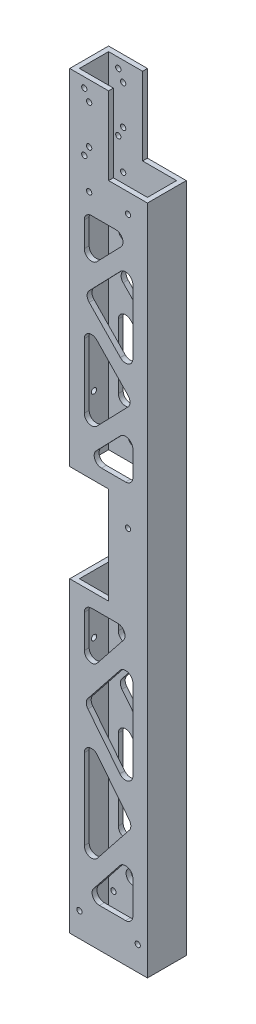
SolidWorks part; units mm, degrees
material "6061-T6 (SS)"
ref_plane "Front Plane" through (0, 0, 0) normal (0, 0, 1) x (1, 0, 0)
ref_plane "Top Plane" through (0, 0, 0) normal (0, 1, 0) x (1, 0, 0)
ref_plane "Right Plane" through (0, 0, 0) normal (1, 0, 0) x (0, 0, -1)
sketch "Sketch1" plane through (0, 0, 0) normal (0, 1, 0) x (1, 0, 0)
  line L0 (-22.225, 9.525) -> (-22.225, 12.7) construction
  line L1 (-25.4, -12.7) -> (25.4, -12.7)
  line L2 (-25.4, -12.7) -> (-25.4, 12.7)
  line L3 (-25.4, 12.7) -> (25.4, 12.7)
  line L4 (25.4, -12.7) -> (25.4, 12.7)
  line L5 (-25.4, -12.7) -> (25.4, 12.7) construction
  line L6 (-25.4, 12.7) -> (25.4, -12.7) construction
  line L7 (-22.225, -9.525) -> (22.225, -9.525)
  line L8 (-22.225, -9.525) -> (-22.225, 9.525)
  line L9 (-22.225, 9.525) -> (22.225, 9.525)
  line L10 (22.225, -9.525) -> (22.225, 9.525)
  line L11 (-22.225, -9.525) -> (22.225, 9.525) construction
  line L12 (-22.225, 9.525) -> (22.225, -9.525) construction
  line L13 (-22.225, 9.525) -> (-25.4, 9.525) construction
  point P0 (0, 0)
  point P6 (0, 0)
  dimension "D1" = 50.8
  dimension "D2" = 25.4
  dimension "D3" = 3.175
extrude "Boss-Extrude1" add sketch "Sketch1" along normal mid plane 489.585
sketch "Sketch2" plane through (0, 0, 12.7) normal (0, 0, 1) x (1, 0, 0)
  line L1 (25.4, 244.7925) -> (0, 244.7925)
  line L2 (25.4, 244.7925) -> (25.4, 193.9925)
  line L3 (25.4, 193.9925) -> (0, 193.9925)
  line L4 (0, 244.7925) -> (0, 193.9925)
  dimension "D1" = 25.4
  dimension "D2" = 50.8
extrude "Cut-Extrude1" cut sketch "Sketch2" against normal through all contours L3 L4 L1 L2
sketch "Sketch3" plane through (0, 0, 12.7) normal (0, 0, 1) x (1, 0, 0)
  line L0 (-25.4, 244.7925) -> (-25.4, -244.7925) construction
  line L1 (-25.4, -44.1325) -> (0, -44.1325)
  line L2 (-25.4, -44.1325) -> (-25.4, 19.3675)
  line L3 (-25.4, 19.3675) -> (0, 19.3675)
  line L4 (0, -44.1325) -> (0, 19.3675)
  line L5 (25.4, -244.7925) -> (-25.4, -244.7925) construction
  dimension "D1" = 63.5
  dimension "D2" = 25.4
  dimension "D3" = 200.66
extrude "Cut-Extrude2" cut sketch "Sketch3" against normal through all
hole_wizard "#8-32 Tapped Hole1" positions "Sketch5" profile "Sketch4" tap size "#8-32" standard "ANSI Inch" end condition through all
sketch "Sketch5" plane through (0, 0, -12.7) normal (0, 0, -1) x (-1, 0, 0)
  line L0 (12.7, 244.7925) -> (12.7, 50244.7925) construction
  line L1 (0, 244.7925) -> (25.4, 244.7925) construction
  line L2 (5.858, 181.2925) -> (-49994.142, 181.2925) construction
  line L3 (0, 192.4017) -> (0, 50192.4017) construction
  line L4 (0, 244.7925) -> (0, 193.9925) construction
  line L5 (12.7, 181.2925) -> (12.7, 206.6925) construction
  line L6 (12.7, 206.6925) -> (12.7, 232.0925) construction
  line L7 (12.7, 232.0925) -> (12.7, 244.7925) construction
  point P0 (12.7, 232.0925)
  point P2 (12.7, 206.6925)
  point P4 (12.7, 181.2925)
  point P6 (-12.7, 181.2925)
  point P13 (12.7, 244.7925)
  dimension "D1" = 25.4
  dimension "D2" = 25.4
  dimension "D3" = 12.7
sketch "Sketch4" plane through (-12.7, 232.0925, -12.7) normal (1, 0, 0) x (0, 1, 0)
  line L0 (0, 0) -> (0, 25.4)
  line L1 (0, 25.4) -> (1.7272, 25.4)
  line L2 (1.7272, 25.4) -> (1.7272, 0)
  line L5 (1.7272, 0) -> (0, 0)
  line L11 (0, -6.35) -> (0, 107.95) construction
  dimension "Thru Tap Drill Dia." = 3.4544
  dimension "Thru Tap Drill Depth" = 25.4
cosmetic thread "Hole Thread1" parameters "D2"=4.1656
cosmetic thread "Hole Thread2" parameters "D2"=4.1656
cosmetic thread "Hole Thread3" parameters "D2"=4.1656
cosmetic thread "Hole Thread4" parameters "D2"=4.1656
hole_wizard "#8-32 Tapped Hole2" positions "Sketch7" profile "Sketch6" tap size "#8-32" standard "ANSI Inch" end condition through all
sketch "Sketch7" plane through (0, 0, 12.7) normal (0, 0, 1) x (1, 0, 0)
  line L0 (-15.875, 200.3425) -> (-15.875, 50200.3425) construction
  line L1 (0, 219.3925) -> (-50000, 219.3925) construction
  line L2 (0, 244.7925) -> (0, 193.9925) construction
  point P0 (-15.875, 238.4425)
  point P2 (-15.875, 200.3425)
  point P11 (0, 219.3925)
  dimension "D1" = 38.1
  dimension "D2" = 15.875
sketch "Sketch6" plane through (-15.875, 238.4425, 12.7) normal (1, 0, 0) x (0, -1, 0)
  line L0 (0, 0) -> (0, 25.4)
  line L1 (0, 25.4) -> (1.7272, 25.4)
  line L2 (1.7272, 25.4) -> (1.7272, 0)
  line L5 (1.7272, 0) -> (0, 0)
  line L11 (0, -6.35) -> (0, 107.95) construction
  dimension "Thru Tap Drill Dia." = 3.4544
  dimension "Thru Tap Drill Depth" = 25.4
cosmetic thread "Hole Thread5" parameters "D2"=4.1656
cosmetic thread "Hole Thread6" parameters "D2"=4.1656
sketch "Sketch8" plane through (0, 0, 12.7) normal (0, 0, 1) x (1, 0, 0)
  line L0 (15.875, -179.4538) -> (15.875, -219.3925)
  line L1 (15.875, -219.3925) -> (-15.875, -219.3925)
  line L2 (-15.875, -219.3925) -> (15.875, -179.4538)
  line L5 (-25.4, -244.7925) -> (25.4, -244.7925) construction
  line L55 (1.209, 168.5925) -> (-49998.791, 168.5925) construction
  line L56 (-15.875, 168.5925) -> (15.875, 168.5925)
  line L57 (15.875, 168.5925) -> (-15.875, 135.7335)
  line L58 (-15.875, 135.7335) -> (-15.875, 168.5925)
  line L59 (-15.875, 122.0258) -> (15.875, 154.8848)
  line L60 (15.875, 154.8848) -> (15.875, 89.1668)
  line L61 (15.875, 89.1668) -> (-15.875, 122.0258)
  line L62 (-15.875, 108.3182) -> (15.875, 75.4592)
  line L63 (15.875, 75.4592) -> (-15.875, 42.6002)
  line L64 (-15.875, 42.6002) -> (-15.875, 108.3182)
  line L65 (-9.525, 235.2675) -> (-15.875, 235.2675)
  line L66 (-9.525, 184.4675) -> (-9.525, 235.2675)
  line L67 (15.875, 184.4675) -> (-9.525, 184.4675)
  line L68 (15.875, -235.2675) -> (15.875, 184.4675)
  line L69 (-15.875, -235.2675) -> (15.875, -235.2675)
  line L70 (-15.875, -53.6575) -> (-15.875, -235.2675)
  line L71 (9.525, -53.6575) -> (-15.875, -53.6575)
  line L72 (9.525, 28.8925) -> (9.525, -53.6575)
  line L73 (-15.875, 28.8925) -> (9.525, 28.8925)
  line L74 (-15.875, 235.2675) -> (-15.875, 28.8925)
  line L75 (-9.525, 235.2675) -> (-15.875, 235.2675) construction
  line L76 (-9.525, 184.4675) -> (-9.525, 235.2675) construction
  line L77 (15.875, 184.4675) -> (-9.525, 184.4675) construction
  line L78 (15.875, -235.2675) -> (15.875, 184.4675) construction
  line L79 (-15.875, -235.2675) -> (15.875, -235.2675) construction
  line L80 (-15.875, -53.6575) -> (-15.875, -235.2675) construction
  line L81 (9.525, -53.6575) -> (-15.875, -53.6575) construction
  line L82 (9.525, 28.8925) -> (9.525, -53.6575) construction
  line L83 (-15.875, 28.8925) -> (9.525, 28.8925) construction
  line L84 (-15.875, 235.2675) -> (-15.875, 28.8925) construction
  line L85 (-15.875, 28.8925) -> (15.875, 28.8925)
  line L86 (15.875, 28.8925) -> (15.875, 61.7515)
  line L87 (15.875, 61.7515) -> (-15.875, 28.8925)
  line L88 (-15.875, 135.7335) -> (-15.875, 108.3182) construction
  line L89 (15.875, 89.1668) -> (15.875, 61.7515) construction
  line L90 (15.875, 61.7515) -> (15.6894, 49.1955)
  line L91 (-15.875, -53.6575) -> (15.875, -53.6575)
  line L92 (15.875, -53.6575) -> (-15.875, -93.5962)
  line L93 (-15.875, -93.5962) -> (-15.875, -53.6575)
  line L94 (15.875, -68.9638) -> (-15.875, -108.9025)
  line L95 (-15.875, -108.9025) -> (15.875, -148.8412)
  line L96 (15.875, -148.8412) -> (15.875, -68.9638)
  line L97 (-15.875, -124.2088) -> (15.875, -164.1475)
  line L98 (15.875, -164.1475) -> (-15.875, -204.0862)
  line L99 (-15.875, -204.0862) -> (-15.875, -124.2088)
  line L103 (15.875, -148.8412) -> (15.875, -179.4538) construction
  line L104 (-15.875, -93.5962) -> (-15.875, -124.2088) construction
  dimension "D2" = 76.2
  dimension "D3" = 9.525
  dimension "D4" = 9.525
  dimension "D5" = 25.4
  dimension "D1" = 9.525
extrude "Cut-Extrude3" cut sketch "Sketch8" against normal through all
fillet "Fillet1" radius 4.7625 48 edges at (-15.875, 168.5925, -11.1125) (15.875, 168.5925, -11.1125) (-15.875, 135.7335, -11.1125) (-15.875, 108.3182, -11.1125) (15.875, 75.4592, -11.1125) (-15.875, 42.6002, -11.1125) (-15.875, 28.8925, -11.1125) (15.875, 61.7515, -11.1125) (15.875, 28.8925, -11.1125) (-15.875, -124.2088, -11.1125) (15.875, -164.1475, -11.1125) (-15.875, -204.0862, -11.1125) (15.875, -68.9638, -11.1125) (15.875, -148.8412, -11.1125) (-15.875, -108.9025, -11.1125) (-15.875, -53.6575, -11.1125) (15.875, -53.6575, -11.1125) (-15.875, -93.5962, -11.1125) (-15.875, 122.0258, -11.1125) (15.875, 154.8848, -11.1125) (15.875, 89.1668, -11.1125) (15.875, 168.5925, 11.1125) (-15.875, 135.7335, 11.1125) (-15.875, 168.5925, 11.1125) (15.875, 75.4592, 11.1125) (-15.875, 42.6002, 11.1125) (-15.875, 108.3182, 11.1125) (15.875, 28.8925, 11.1125) (-15.875, 28.8925, 11.1125) (15.875, 61.7515, 11.1125) (15.875, -164.1475, 11.1125) (-15.875, -204.0862, 11.1125) (-15.875, -124.2088, 11.1125) (-15.875, -108.9025, 11.1125) (15.875, -68.9638, 11.1125) (15.875, -148.8412, 11.1125) (15.875, -53.6575, 11.1125) (-15.875, -93.5962, 11.1125) (-15.875, -53.6575, 11.1125) (15.875, 154.8848, 11.1125) (15.875, 89.1668, 11.1125) (-15.875, 122.0258, 11.1125) (15.875, -179.4538, 11.1125) (15.875, -179.4538, -11.1125) (15.875, -219.3925, 11.1125) (15.875, -219.3925, -11.1125) (-15.875, -219.3925, -11.1125) (-15.875, -219.3925, 11.1125)
hole_wizard "#8-32 Tapped Hole3" positions "Sketch10" profile "Sketch9" tap size "#8-32" standard "ANSI Inch" end condition through all
sketch "Sketch10" plane through (0, 0, 12.7) normal (0, 0, 1) x (1, 0, 0)
  line L1 (25.4, 3.4925) -> (0, 3.4925)
  line L2 (25.4, 193.9925) -> (25.4, -244.7925) construction
  line L3 (0, -44.1325) -> (0, 19.3675) construction
  line L5 (0, -12.3825) -> (-50000, -12.3825) construction
  line L6 (-25.4, -244.7925) -> (25.4, -244.7925) construction
  point P0 (12.7, 3.4925)
  dimension "D1" = 15.875
  dimension "D2" = 232.41
sketch "Sketch9" plane through (12.7, 3.4925, 12.7) normal (1, 0, 0) x (0, -1, 0)
  line L0 (0, 0) -> (0, 25.4)
  line L1 (0, 25.4) -> (1.7272, 25.4)
  line L2 (1.7272, 25.4) -> (1.7272, 0)
  line L5 (1.7272, 0) -> (0, 0)
  line L11 (0, -6.35) -> (0, 107.95) construction
  dimension "Thru Tap Drill Dia." = 3.4544
  dimension "Thru Tap Drill Depth" = 25.4
cosmetic thread "Hole Thread7" parameters "D2"=4.1656
hole_wizard "#8-32 Tapped Hole4" positions "Sketch12" profile "Sketch11" tap size "#8-32" standard "ANSI Inch"
sketch "Sketch12" plane through (-25.4, 0, 0) normal (-1, 0, 0) x (0, 0, 1)
  line L0 (0, 0) -> (0, 50000) construction
  line L1 (0, 57.4675) -> (0, 32.0675) construction
  line L2 (0, 32.0675) -> (0, 19.3675) construction
  line L4 (-12.7, 19.3675) -> (12.7, 19.3675) construction
  line L5 (0, -82.2325) -> (0, -56.8325) construction
  line L6 (0, -56.8325) -> (0, -44.1325) construction
  line L8 (-12.7, -44.1325) -> (12.7, -44.1325) construction
  point P0 (0, 32.0675)
  point P2 (0, 57.4675)
  point P4 (0, -56.8325)
  point P6 (0, -82.2325)
  dimension "D1" = 12.7
  dimension "D2" = 25.4
sketch "Sketch11" plane through (-25.4, 32.0675, 0) normal (0, 1, 0) x (0, 0, 1)
  line L0 (0, 0) -> (0, 3.175)
  line L1 (0, 3.175) -> (1.7272, 3.175)
  line L2 (1.7272, 3.175) -> (1.7272, 0)
  line L5 (1.7272, 0) -> (0, 0)
  line L11 (0, -6.35) -> (0, 107.95) construction
  dimension "Thru Tap Drill Dia." = 3.4544
  dimension "Thru Tap Drill Depth" = 3.175
cosmetic thread "Hole Thread8" parameters "D2"=4.1656
cosmetic thread "Hole Thread9" parameters "D2"=4.1656
cosmetic thread "Hole Thread10" parameters "D2"=4.1656
cosmetic thread "Hole Thread11" parameters "D2"=4.1656
hole_wizard "#8-32 Tapped Hole5" positions "Sketch14" profile "Sketch13" tap size "#8-32" standard "ANSI Inch" end condition through all
sketch "Sketch14" plane through (0, 0, 12.7) normal (0, 0, 1) x (1, 0, 0)
  line L0 (0, 0) -> (0, -49985.4086) construction
  line L2 (0.8475, -228.9175) -> (-49999.1525, -228.9175) construction
  line L3 (-25.4, -244.7925) -> (25.4, -244.7925) construction
  point P0 (-19.05, -228.9175)
  point P2 (19.05, -228.9175)
  dimension "D1" = 38.1
  dimension "D2" = 15.875
sketch "Sketch13" plane through (-19.05, -228.9175, 12.7) normal (1, 0, 0) x (0, -1, 0)
  line L0 (0, 0) -> (0, 25.4)
  line L1 (0, 25.4) -> (1.7272, 25.4)
  line L2 (1.7272, 25.4) -> (1.7272, 0)
  line L5 (1.7272, 0) -> (0, 0)
  line L11 (0, -6.35) -> (0, 107.95) construction
  dimension "Thru Tap Drill Dia." = 3.4544
  dimension "Thru Tap Drill Depth" = 25.4
cosmetic thread "Hole Thread12" parameters "D2"=4.1656
cosmetic thread "Hole Thread13" parameters "D2"=4.1656
